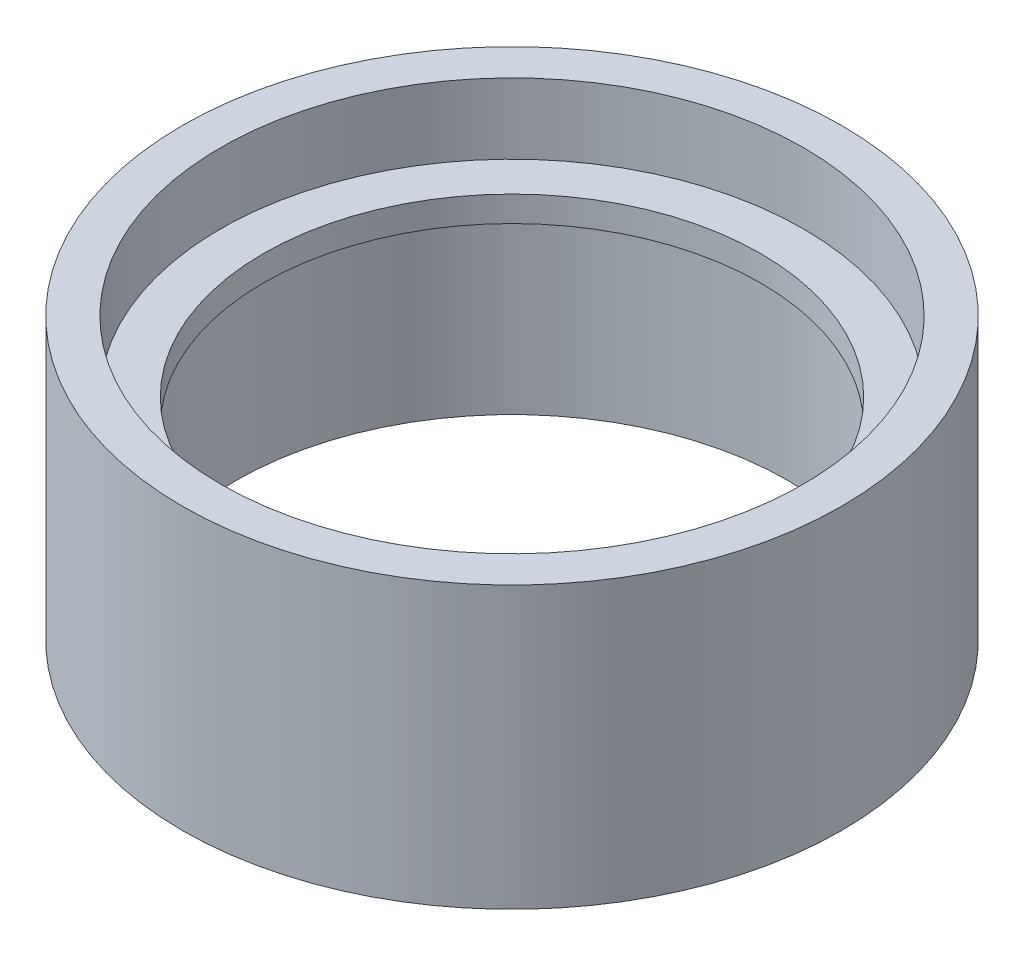
SolidWorks part; units mm, degrees
ref_plane "Front Plane" through (0, 0, 0) normal (0, 0, 1) x (1, 0, 0)
ref_plane "Top Plane" through (0, 0, 0) normal (0, 1, 0) x (1, 0, 0)
ref_plane "Right Plane" through (0, 0, 0) normal (1, 0, 0) x (0, 0, -1)
sketch "Sketch3" plane through (0, 0, 0) normal (0, 1, 0) x (1, 0, 0)
  circle A0 centre (0, 0) radius 29.0195
  circle A1 centre (0, 0) radius 24.765
  dimension "D1" = 58.039
  dimension "D2" = 49.53
extrude "Boss-Extrude2" add sketch "Sketch3" along normal blind 2.54
sketch "Sketch4" plane through (0, 0, 0) normal (0, 1, 0) x (1, 0, 0)
  circle A0 centre (0, 0) radius 29.0195 construction
  circle A1 centre (0, 0) radius 29.0195
  circle A2 centre (0, 0) radius 32.8295
  dimension "D1" = 3.81
extrude "Boss-Extrude3" add sketch "Sketch4" along normal offset from surface (9.5504 mm away) 7.0104 contours A2
sketch "Sketch5" plane through (0, 0, 0) normal (0, -1, 0) x (1, 0, 0)
  circle A0 centre (0, 0) radius 27.5082
  circle A1 centre (0, 0) radius 32.8295
  circle A2 centre (0, 0) radius 32.8295 construction
  dimension "D1" = 55.0164
extrude "Boss-Extrude4" add sketch "Sketch5" along normal blind 18.415
